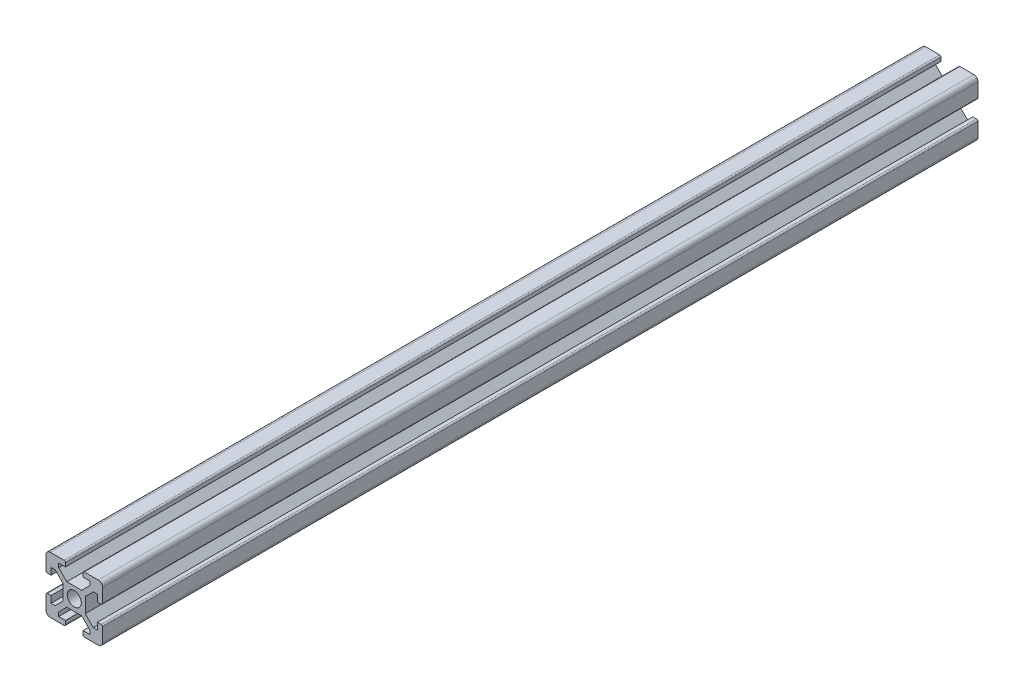
SolidWorks part; units mm, degrees
ref_plane "前视基准面" through (0, 0, 0) normal (0, 0, 1) x (1, 0, 0)
ref_plane "上视基准面" through (0, 0, 0) normal (0, 1, 0) x (1, 0, 0)
ref_plane "右视基准面" through (0, 0, 0) normal (1, 0, 0) x (0, 0, -1)
sketch "草图1" plane through (0, 0, 0) normal (0, 0, 1) x (1, 0, 0)
  line L0 (0, 6.9) -> (0, 0)
  line L1 (20, 20) -> (20, 13.1)
  line L2 (1.8, 15.5) -> (3.2272, 15.5)
  line L3 (4.5, 16.7728) -> (4.5, 18.2)
  line L4 (0, 13.1) -> (0, 20)
  line L5 (6.9, 20) -> (6.9, 18.2)
  line L6 (6.9, 18.2) -> (4.5, 18.2)
  line L7 (13.1, 20) -> (20, 20)
  line L8 (6.9, 20) -> (0, 20)
  line L9 (0, 0) -> (6.9, 0)
  line L10 (13.1, 0) -> (20, 0)
  line L11 (15.5, 18.2) -> (15.5, 16.7728)
  line L12 (16.7728, 15.5) -> (18.2, 15.5)
  line L13 (20, 6.9) -> (20, 0)
  line L14 (1.8, 4.5) -> (3.2272, 4.5)
  line L15 (4.5, 3.2272) -> (4.5, 1.8)
  line L16 (12.6272, 6.1) -> (15.5, 3.2272)
  line L17 (18.2, 4.5) -> (16.7728, 4.5)
  line L18 (15.5, 3.2272) -> (15.5, 1.8)
  line L19 (13.9, 7.3728) -> (16.7728, 4.5)
  line L20 (13.1, 20) -> (13.1, 18.2)
  line L21 (13.1, 18.2) -> (15.5, 18.2)
  line L22 (7.3728, 13.9) -> (12.6272, 13.9)
  line L23 (13.9, 12.6272) -> (13.9, 7.3728)
  line L24 (7.3728, 6.1) -> (12.6272, 6.1)
  line L25 (6.1, 12.6272) -> (6.1, 7.3728)
  line L27 (12.6272, 13.9) -> (15.5, 16.7728)
  line L30 (3.2272, 4.5) -> (6.1, 7.3728)
  line L32 (4.5, 3.2272) -> (7.3728, 6.1)
  line L33 (20, 13.1) -> (18.2, 13.1)
  line L34 (18.2, 13.1) -> (18.2, 15.5)
  line L36 (20, 6.9) -> (18.2, 6.9)
  line L37 (18.2, 6.9) -> (18.2, 4.5)
  line L39 (13.1, 0) -> (13.1, 1.8)
  line L40 (13.1, 1.8) -> (15.5, 1.8)
  line L42 (6.9, 0) -> (6.9, 1.8)
  line L43 (6.9, 1.8) -> (4.5, 1.8)
  line L45 (0, 6.9) -> (1.8, 6.9)
  line L46 (1.8, 6.9) -> (1.8, 4.5)
  line L48 (0, 13.1) -> (1.8, 13.1)
  line L49 (1.8, 13.1) -> (1.8, 15.5)
  line L50 (4.5, 16.7728) -> (7.3728, 13.9)
  line L51 (3.2272, 15.5) -> (6.1, 12.6272)
  line L53 (13.9, 12.6272) -> (16.7728, 15.5)
  line L62 (1.8, 13.1) -> (1.8, 15.5)
  line L63 (0, 13.1) -> (1.8, 13.1)
  line L66 (6.9, 18.2) -> (4.5, 18.2)
  line L67 (6.9, 20) -> (6.9, 18.2)
  line L68 (3.2272, 15.5) -> (1.8, 15.5)
  line L69 (4.5, 18.2) -> (4.5, 16.7728)
  line L75 (4.5, 1.8) -> (4.5, 3.2272)
  line L76 (3.2272, 4.5) -> (1.8, 4.5)
  line L77 (6.9, 0) -> (6.9, 1.8)
  line L78 (6.9, 1.8) -> (4.5, 1.8)
  line L80 (0, 6.9) -> (1.8, 6.9)
  line L81 (1.8, 6.9) -> (1.8, 4.5)
  line L90 (1.8, 6.9) -> (1.8, 4.5)
  line L91 (0, 6.9) -> (1.8, 6.9)
  line L93 (18.2, 6.9) -> (18.2, 4.5)
  line L94 (20, 6.9) -> (18.2, 6.9)
  line L98 (13.1, 1.8) -> (15.5, 1.8)
  line L99 (13.1, 0) -> (13.1, 1.8)
  line L100 (16.7728, 4.5) -> (18.2, 4.5)
  line L101 (15.5, 1.8) -> (15.5, 3.2272)
  line L106 (6.9, 1.8) -> (4.5, 1.8)
  line L107 (6.9, 0) -> (6.9, 1.8)
  line L109 (4.5, 3.2272) -> (4.5, 1.8)
  line L110 (1.8, 4.5) -> (3.2272, 4.5)
  circle A0 centre (10, 10) radius 2.5
extrude "凸台-拉伸1" add sketch "草图1" along normal blind 310 contours L23 L53 L12 L34 L33 L1 L7 L20 L21 L11 L27 L22 L50 L3 L6 L5 L8 L4 L48 L49 L2 L51 L25 L30 L14 L46 L45 L0 L9 L42 L43 L15 L32 L24 L16 L18 L40 L39 L10 L13 L36 L37 L17 L19
fillet "圆角1" radius 1.5 1 edges at (20, 20, 155)
fillet "圆角2" radius 1.5 1 edges at (0, 20, 155)
fillet "圆角3" radius 1.5 1 edges at (0, 0, 155)
fillet "圆角4" radius 1.5 1 edges at (20, 0, 155)
fillet "圆角5" radius 0.5 1 edges at (13.1, 20, 155)
fillet "圆角6" radius 0.5 1 edges at (6.9, 20, 155)
fillet "圆角7" radius 0.5 1 edges at (0, 13.1, 155)
fillet "圆角8" radius 0.5 1 edges at (0, 6.9, 155)
fillet "圆角9" radius 0.5 1 edges at (6.9, 0, 155)
fillet "圆角10" radius 0.5 1 edges at (13.1, 0, 155)
fillet "圆角11" radius 0.5 1 edges at (20, 13.1, 155)
fillet "圆角12" radius 0.5 1 edges at (20, 6.9, 155)
